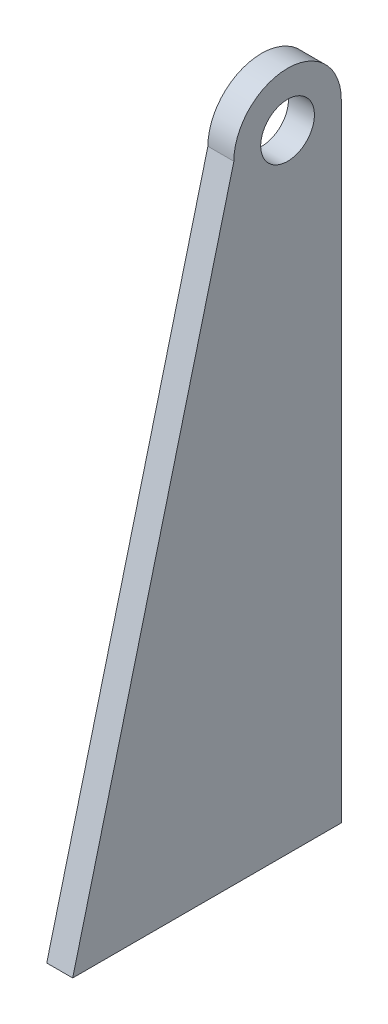
SolidWorks part; units mm, degrees
ref_plane "Front Plane" through (0, 0, 0) normal (0, 0, 1) x (1, 0, 0)
ref_plane "Top Plane" through (0, 0, 0) normal (0, 1, 0) x (1, 0, 0)
ref_plane "Right Plane" through (0, 0, 0) normal (1, 0, 0) x (0, 0, -1)
sketch "Sketch1" plane through (0, 0, 0) normal (1, 0, 0) x (0, 0, -1)
  line L0 (0, 0) -> (60, 0)
  line L1 (60, 0) -> (60, 140)
  line L2 (0, 0) -> (36, 140)
  circle A0 centre (48, 140) radius 6
  arc A1 (60, 140) -> (36, 140) centre (48, 140) ccw
  dimension "D3" = 12
  dimension "D4" = 24
  dimension "D1" = 60
  dimension "D2" = 140
extrude "Boss-Extrude1" add sketch "Sketch1" along normal blind 5.8
